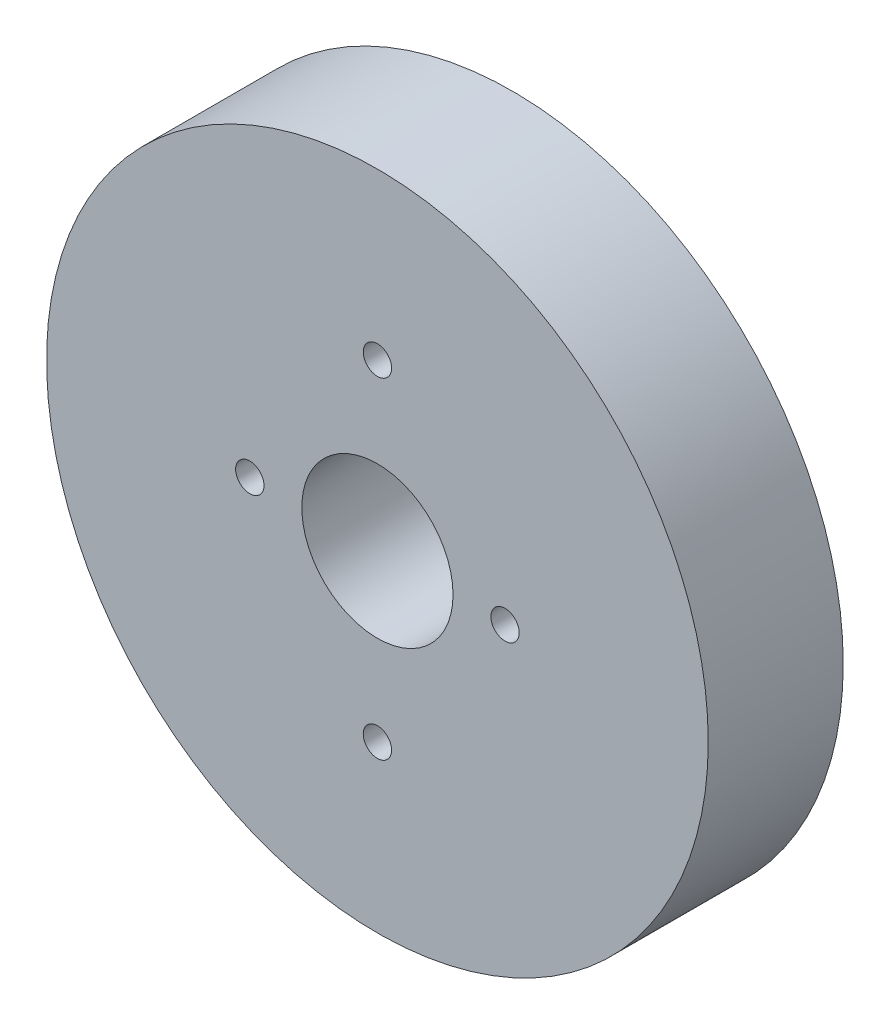
SolidWorks part; units mm, degrees
ref_plane "前视基准面" through (0, 0, 0) normal (0, 0, 1) x (1, 0, 0)
ref_plane "上视基准面" through (0, 0, 0) normal (0, 1, 0) x (1, 0, 0)
ref_plane "右视基准面" through (0, 0, 0) normal (1, 0, 0) x (0, 0, -1)
sketch "草图1" plane through (0, 0, 0) normal (0, 0, 1) x (1, 0, 0)
  line L0 (0, 0) -> (24.8546, 0) construction
  line L1 (0, 0) -> (0, 8.75) construction
  circle A0 centre (0, 0) radius 17.5
  circle A1 centre (0, 0) radius 4
  circle A2 centre (6.75, 0) radius 0.75
  circle A3 centre (0, 8.75) radius 0.75
  circle A4 centre (-6.75, 0) radius 0.75
  circle A5 centre (0, -8.75) radius 0.75
  dimension "D1" = 8
  dimension "D2" = 35
  dimension "D3" = 1.5
  dimension "D4" = 6.75
  dimension "D5" = 8.75
extrude "凸台-拉伸1" add sketch "草图1" along normal blind 7.14
